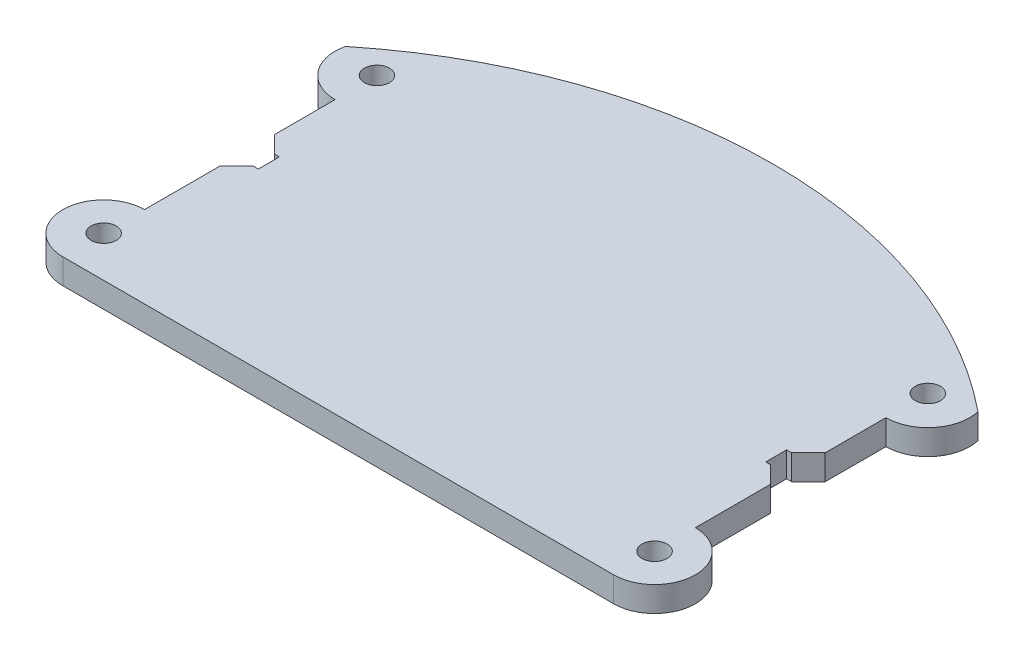
SolidWorks part; units mm, degrees
ref_plane "Alzado" through (0, 0, 0) normal (0, 0, 1) x (1, 0, 0)
ref_plane "Planta" through (0, 0, 0) normal (0, 1, 0) x (1, 0, 0)
ref_plane "Vista lateral" through (0, 0, 0) normal (1, 0, 0) x (0, 0, -1)
sketch "Croquis1" plane through (0, 0, 0) normal (0, 1, 0) x (1, 0, 0)
  line L5 (-32.89, -7.25) -> (-32.89, 0.009)
  line L6 (-32.89, -32.5) -> (32.89, -32.5)
  line L7 (32.89, -22.7466) -> (32.89, -13.7495)
  line L14 (32.89, -13.7495) -> (30.89, -11.7495)
  line L15 (-32.89, -7.25) -> (-30.89, -9.25)
  line L16 (-23.8665, -10.5) -> (-32.89, -10.5) construction
  line L18 (-30.89, -11.7495) -> (-30.29, -11.7495)
  line L20 (-30.89, -9.25) -> (-30.29, -9.25)
  line L21 (-30.29, -11.7495) -> (-30.29, -9.25)
  line L22 (-32.89, -22.7466) -> (-32.89, -13.7495)
  line L24 (-32.89, -13.7495) -> (-30.89, -11.7495)
  line L25 (0, 82.6575) -> (0, -120.6448) construction
  line L26 (30.89, -11.7495) -> (30.29, -11.7495)
  line L27 (30.29, -11.7495) -> (30.29, -9.25)
  line L28 (30.89, -9.25) -> (30.29, -9.25)
  line L29 (32.89, -7.25) -> (30.89, -9.25)
  line L30 (32.89, -7.25) -> (32.89, 0.009)
  line L31 (-32.892, 0.009) -> (-32.89, 0.009)
  line L33 (32.892, 0.009) -> (32.89, 0.009)
  line L36 (-37.7667, 6.1215) -> (-37.7667, -34.0151) construction
  arc A0 (37.7667, 6.1215) -> (-37.7667, 6.1215) centre (0, -40.5012) ccw
  arc A4 (-37.7667, 6.1215) -> (-32.892, 0.009) centre (-32.892, 5.009) ccw construction
  arc A8 (-37.7667, 6.1215) -> (-32.892, 0.009) centre (-32.892, 5.009) ccw
  arc A11 (37.7667, 6.1215) -> (32.892, 0.009) centre (32.892, 5.009) cw
  circle A12 centre (-32.892, 5.009) radius 1.5 construction
  circle A13 centre (32.89, 5.009) radius 1.5 construction
  arc A14 (59.5975, -33.5632) -> (-59.5975, -33.5632) centre (0, -40.5012) ccw construction
  circle A15 centre (-32.892, 5.009) radius 1.5
  circle A16 centre (32.89, 5.009) radius 1.5
  arc A17 (-32.89, -22.7466) -> (-32.89, -32.5) centre (-32.89, -27.6233) ccw
  arc A18 (32.89, -22.7466) -> (32.89, -32.5) centre (32.89, -27.6233) cw
  circle A19 centre (-32.89, -27.6233) radius 1.5
  circle A20 centre (32.89, -27.6233) radius 1.5
  point P0 (0, 0)
  point P3 (0, -32.5)
  point P15 (0, 6.9666)
  dimension "D5" = 2.6
  dimension "D4" = 32.5
  dimension "D8" = 3
  dimension "D9" = 3
  dimension "D1" = 2
  dimension "D2" = 2.4995
  dimension "D3" = 2
  dimension "D6" = 7.25
  dimension "D7" = 32.89
extrude "Saliente-Extruir1" add sketch "Croquis1" along normal blind 3
